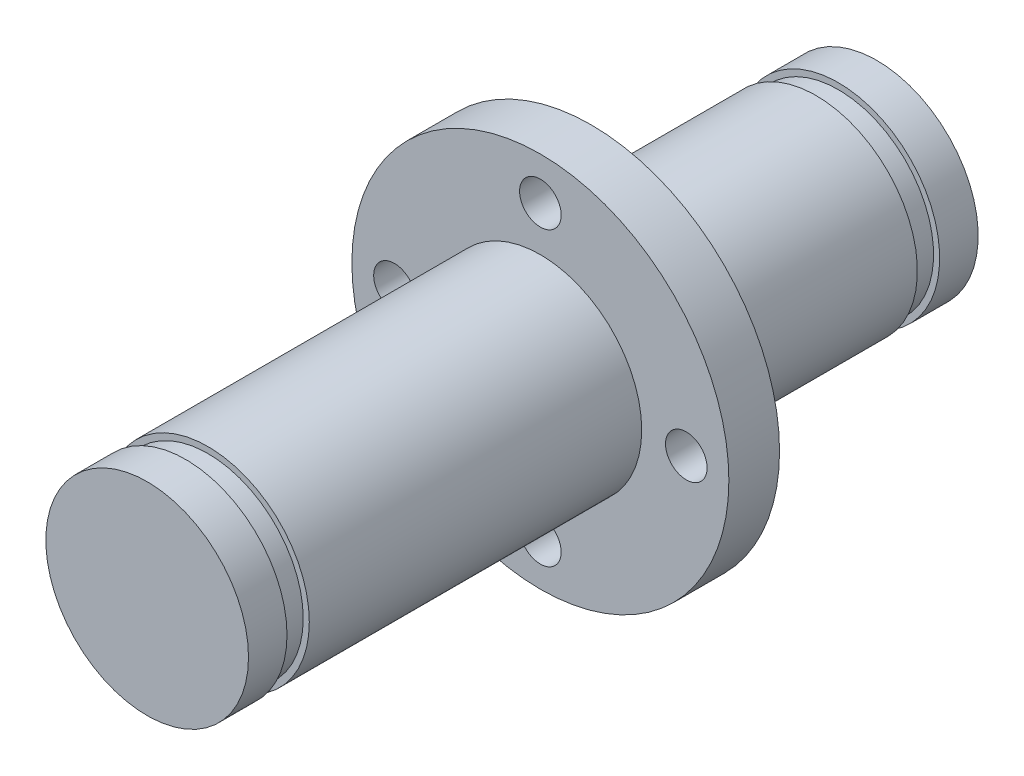
SolidWorks part; units mm, degrees
material "6061 合金"
ref_plane "前视基准面" through (0, 0, 0) normal (0, 0, 1) x (1, 0, 0)
ref_plane "上视基准面" through (0, 0, 0) normal (0, 1, 0) x (1, 0, 0)
ref_plane "右视基准面" through (0, 0, 0) normal (1, 0, 0) x (0, 0, -1)
sketch "草图1" plane through (0, 0, 0) normal (0, 0, 1) x (1, 0, 0)
  circle A0 centre (0, 0) radius 5
extrude "凸台-拉伸1" add sketch "草图1" along normal blind 19.4
sketch "草图2" plane through (0, 0, 0) normal (0, 0, -1) x (-1, 0, 0)
  circle A0 centre (0, 0) radius 9.3
  circle A1 centre (0, 0) radius 7.2 construction
  circle A2 centre (0, 7.2) radius 1.25 construction
  circle A3 centre (7.2, 0) radius 1.25 construction
  circle A4 centre (0, -7.2) radius 1.25 construction
  circle A5 centre (-7.2, 0) radius 1.25 construction
  point P15 (0, 0)
  dimension "D1" = 4
extrude "凸台-拉伸2" add sketch "草图2" along normal blind 2.5
sketch "草图3" plane through (0, 0, -2.5) normal (0, 0, -1) x (-1, 0, 0)
  circle A0 centre (0, 0) radius 5
extrude "凸台-拉伸3" add sketch "草图3" along normal blind 14.1
sketch "草图5" plane through (0, 0, 0) normal (0, 1, 0) x (1, 0, 0)
  line L0 (5, 16.6) -> (5, 13.6) construction
  line L1 (5, 2.5) -> (5, 16.6) construction
  line L2 (0, 16.6) -> (0, 3.845) construction
  line L3 (5, 13.6) -> (4.7, 13.6)
  line L4 (5, 13.6) -> (5, 14.7)
  line L5 (5, 14.7) -> (4.7, 14.7)
  line L6 (4.7, 13.6) -> (4.7, 14.7)
  line L7 (5, 16.6) -> (-5, 16.6) construction
  dimension "D1" = 1.1
  dimension "D2" = 0.3
revolve "切除-旋转3" cut sketch "草图5" angle 360 about L2
sketch "草图6" plane through (0, 0, 0) normal (0, 1, 0) x (1, 0, 0)
  line L0 (5, -19.4) -> (5, -16.4) construction
  line L1 (5, -19.4) -> (5, 0) construction
  line L2 (0, -19.4) -> (0, -10.0207) construction
  line L3 (5, -16.4) -> (4.7, -16.4)
  line L4 (5, -16.4) -> (5, -17.5)
  line L5 (5, -17.5) -> (4.7, -17.5)
  line L6 (4.7, -16.4) -> (4.7, -17.5)
  line L7 (-5, -19.4) -> (5, -19.4) construction
  dimension "D1" = 1.1
  dimension "D2" = 0.3
revolve "切除-旋转4" cut sketch "草图6" angle 360 about L2
sketch "草图9" plane through (0, 0, -2.5) normal (0, 0, -1) x (-1, 0, 0)
  circle A0 centre (0, 0) radius 7.2 construction
  circle A1 centre (0, 7.2) radius 1
  circle A2 centre (7.2, 0) radius 1
  circle A3 centre (0, -7.2) radius 1
  circle A4 centre (-7.2, 0) radius 1 construction
hole_wizard "M2.5 螺纹孔2" positions "3D草图4" profile "草图11" tap size "M2.5" standard "GB"
sketch3d "3D草图4"
  point P0 (0, 7.2, -2.5)
  point P3 (-7.2, 0, -2.5)
  point P6 (7.2, 0, -2.5)
  point P9 (0, -7.2, -2.5)
sketch "草图11" plane through (0, 7.2, -2.5) normal (1, 0, 0) x (0, 1, 0)
  line L0 (0, 0) -> (0, 7.8418)
  line L1 (0, 7.8418) -> (1.025, 7.25)
  line L2 (1.025, 7.25) -> (1.025, 0)
  line L5 (1.025, 0) -> (0, 0)
  line L10 (0, 7.8418) -> (-1.025, 7.25) construction
  line L11 (0, -6.35) -> (0, 107.95) construction
  dimension "螺纹孔钻头直径" = 2.05
  dimension "螺纹孔钻头深度" = 7.25
  dimension "导头角度" = 120
cosmetic thread "孔螺蚊线1" parameters "D1"=2.5, "D2"=2.5
cosmetic thread "孔螺蚊线2" parameters "D1"=2.5, "D2"=2.5
cosmetic thread "孔螺蚊线3" parameters "D1"=2.5, "D2"=2.5
cosmetic thread "孔螺蚊线4" parameters "D1"=2.5, "D2"=2.5
sketch "草图12" plane through (0, 0, -16.6) normal (0, 0, -1) x (-1, 0, 0)
  circle A0 centre (0, 0) radius 2
extrude "切除-拉伸1" cut sketch "草图12" against normal blind 28
